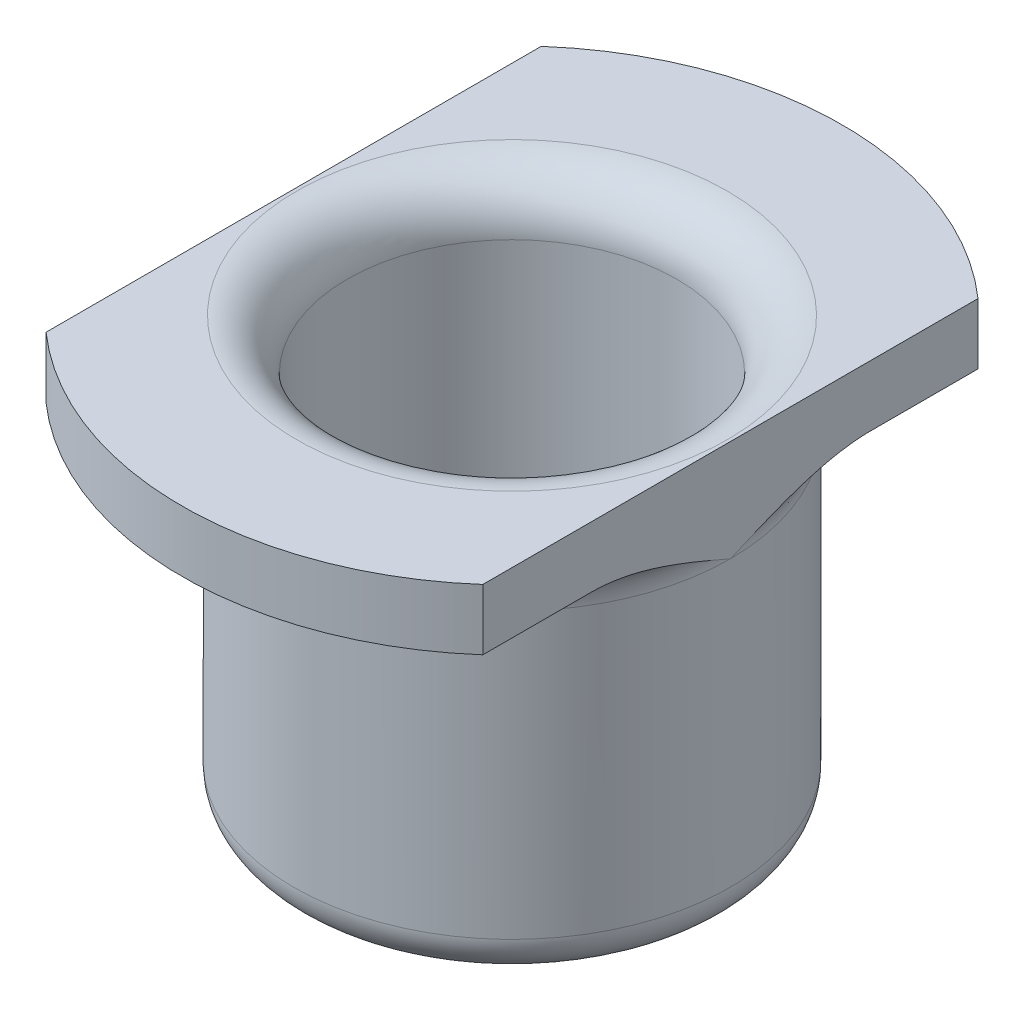
SolidWorks part; units mm, degrees
ref_plane "Plano frontal" through (0, 0, 0) normal (0, 0, 1) x (1, 0, 0)
ref_plane "Plano superior" through (0, 0, 0) normal (0, 1, 0) x (1, 0, 0)
ref_plane "Plano direito" through (0, 0, 0) normal (1, 0, 0) x (0, 0, -1)
sketch "Esboço1" plane through (0, 0, 0) normal (0, 0, 1) x (1, 0, 0)
  line L0 (0, 66.8262) -> (0, -69.6953) construction
  line L1 (8.1, -2.3115) -> (8.1, -20.3115)
  line L2 (8.1, -20.3115) -> (5.35, -20.3115)
  line L3 (5.35, -20.3115) -> (5.35, -23.3115)
  line L4 (5.35, -23.3115) -> (10.75, -23.3115)
  line L5 (10.75, -23.3115) -> (10.75, -5.3115)
  line L6 (10.75, -5.3115) -> (16.25, -5.3115)
  line L7 (16.25, -5.3115) -> (16.25, -2.3115)
  line L8 (16.25, -2.3115) -> (8.1, -2.3115)
  dimension "D1" = 5.35
  dimension "D2" = 10.75
  dimension "D3" = 8.1
  dimension "D4" = 16.25
  dimension "D5" = 18
  dimension "D6" = 3
  dimension "D7" = 21
revolve "Revolução1" add sketch "Esboço1" angle 360 about L0
fillet "Filete1" radius 2.5 1 edges at (0, -2.3115, 8.1)
fillet "Filete2" radius 1.5 1 edges at (0, -20.3115, 8.1)
fillet "Filete3" radius 2 1 edges at (0, -23.3115, 10.75)
fillet "Filete4" radius 2 1 edges at (0, -5.3115, 10.75)
sketch "Esboço3" plane through (0, -5.3115, 0) normal (0, -1, 0) x (1, 0, 0)
  line L0 (-10.75, 0) -> (-10.75, -18.4001)
  line L1 (10.75, 0) -> (10.75, -18.4001)
  line L2 (10.75, -18.4001) -> (-10.75, -18.4001)
  line L3 (-10.75, 0) -> (-10.75, 16.9702)
  line L4 (-10.75, 16.9702) -> (10.75, 16.9702)
  line L5 (10.75, 16.9702) -> (10.75, 0)
  circle A0 centre (0, 0) radius 10.75 construction
extrude "Corte-extrusão2" cut sketch "Esboço3" against normal blind 10 and the other way blind 10 flip side to cut
